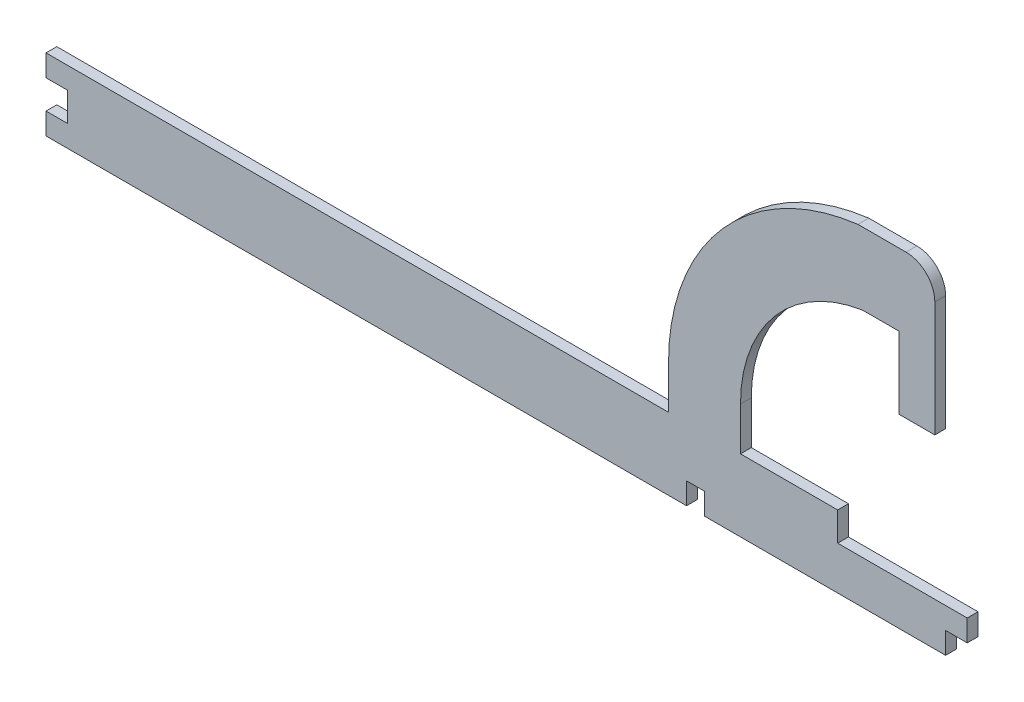
SolidWorks part; units mm, degrees
ref_plane "Спереди" through (0, 0, 0) normal (0, 0, 1) x (1, 0, 0)
ref_plane "Сверху" through (0, 0, 0) normal (0, 1, 0) x (1, 0, 0)
ref_plane "Справа" through (0, 0, 0) normal (1, 0, 0) x (0, 0, -1)
sketch "Эскиз2" plane through (0, 0, 0) normal (0, 0, 1) x (1, 0, 0)
  line L1 (0, 0) -> (172, 0)
  line L2 (0, 0) -> (0, 20) construction
  line L18 (244, 12) -> (244, 0) construction
  line L33 (0, 20) -> (167, 20)
  line L35 (187, 20) -> (187, 32)
  line L36 (187, 32) -> (167, 32) construction
  line L37 (167, 32) -> (167, 20)
  line L38 (231, 71.5474) -> (231, 51.5474)
  line L39 (231, 51.5474) -> (241, 51.5474)
  line L42 (187, 20) -> (214, 20)
  line L44 (241, 83.5474) -> (241, 51.5474)
  line L45 (231, 71.5474) -> (221, 71.5474)
  line L46 (233, 91.5474) -> (219.6446, 91.5474)
  line L47 (214, 20) -> (214, 12)
  line L48 (214, 12) -> (244, 12)
  line L49 (0, 20) -> (-6, 20)
  line L50 (-6, 20) -> (-6, 14)
  line L51 (-6, 14) -> (0, 14)
  line L52 (0, 14) -> (0, 6)
  line L53 (0, 6) -> (-6, 6)
  line L54 (-6, 6) -> (-6, 0)
  line L55 (-6, 0) -> (0, 0)
  line L56 (244, 12) -> (250, 12)
  line L57 (250, 12) -> (250, 6)
  line L58 (250, 6) -> (244, 6)
  line L59 (244, 6) -> (244, 0)
  line L60 (177, 0) -> (244, 0)
  line L62 (177, 0) -> (177, 6)
  line L63 (177, 6) -> (172, 6)
  line L64 (172, 0) -> (172, 6)
  arc A2 (241, 83.5474) -> (233, 91.5474) centre (233, 83.5474) ccw
  arc A7 (221, 71.5474) -> (187, 32) centre (227, 32) ccw
  arc A8 (219.6446, 91.5474) -> (167, 32) centre (227, 32) ccw
  dimension "D3" = 12
  dimension "D4" = 20
  dimension "D5" = 10
  dimension "D8" = 80
  dimension "D9" = 20
  dimension "D1" = 244
  dimension "D2" = 20
  dimension "D6" = 3
  dimension "D7" = 10
  dimension "D10" = 20
  dimension "D11" = 8
  dimension "D12" = 17
  dimension "D13" = 8
  dimension "D14" = 30
  dimension "D15" = 6
  dimension "D16" = 6
  dimension "D17" = 6
  dimension "D18" = 6
  dimension "D19" = 67
  dimension "D20" = 6
  dimension "D21" = 5
extrude "Бобышка-Вытянуть1" add sketch "Эскиз2" along normal blind 3
